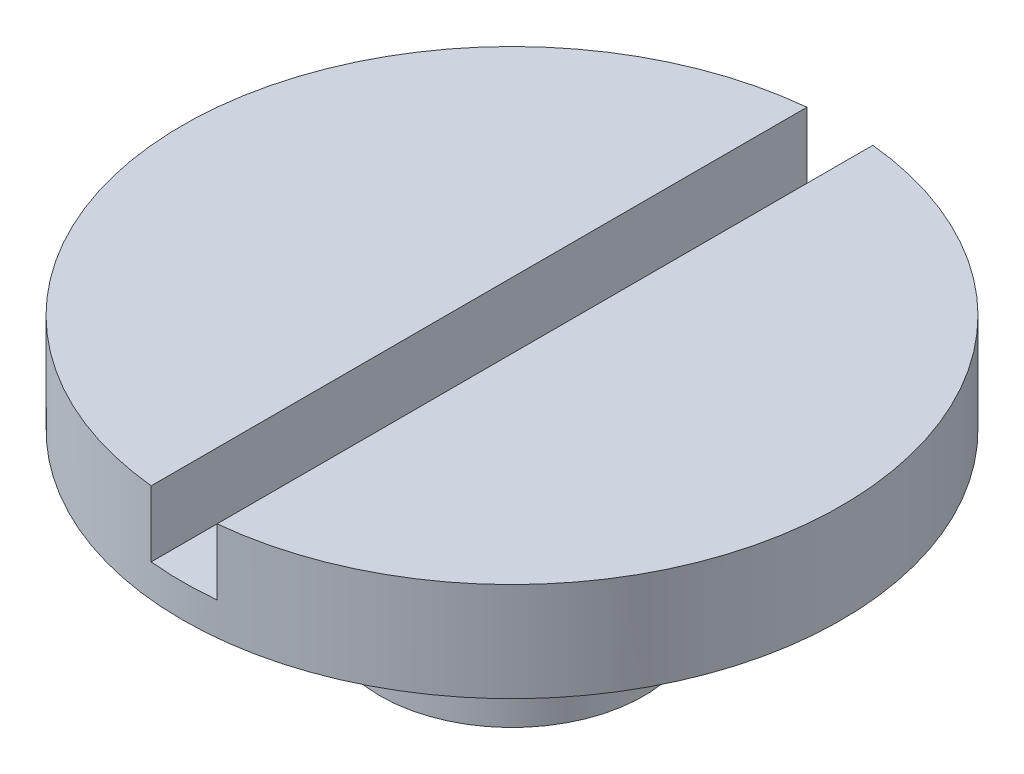
SolidWorks part; units mm, degrees
ref_plane "Front Plane" through (0, 0, 0) normal (0, 0, 1) x (1, 0, 0)
ref_plane "Top Plane" through (0, 0, 0) normal (0, 1, 0) x (1, 0, 0)
ref_plane "Right Plane" through (0, 0, 0) normal (1, 0, 0) x (0, 0, -1)
sketch "Sketch1" plane through (0, 0, 0) normal (0, 1, 0) x (1, 0, 0)
  circle A0 centre (0, 0) radius 50
  dimension "D1" = 100
extrude "Boss-Extrude1" add sketch "Sketch1" along normal blind 15
sketch "Sketch2" plane through (0, 15, 0) normal (0, 1, 0) x (1, 0, 0)
  line L0 (0, 50) -> (0, -50) construction
  line L1 (-5, 49.7494) -> (-5, -49.7494)
  line L2 (5, 49.7494) -> (5, -49.7494)
  circle A0 centre (0, 0) radius 50 construction
  arc A1 (-5, -49.7494) -> (5, -49.7494) centre (0, 0) ccw
  arc A2 (5, 49.7494) -> (-5, 49.7494) centre (0, 0) ccw
  point P7 (0, 0)
  dimension "D1" = 10
extrude "Cut-Extrude1" cut sketch "Sketch2" against normal blind 10
sketch "Sketch3" plane through (0, 0, 0) normal (0, -1, 0) x (1, 0, 0)
  line L0 (0, 0) -> (0, 26.5345) construction
  line L1 (3, 14.6969) -> (3, 18.6969)
  line L2 (3, 18.6969) -> (-3, 18.6969)
  line L3 (-3, 14.6969) -> (-3, 18.6969)
  circle A0 centre (0, 0) radius 15
  circle A1 centre (0, 0) radius 20
  point P10 (0, 18.6969)
  dimension "D1" = 30
  dimension "D2" = 40
  dimension "D3" = 6
  dimension "D4" = 4
extrude "Boss-Extrude2" add sketch "Sketch3" along normal blind 25
